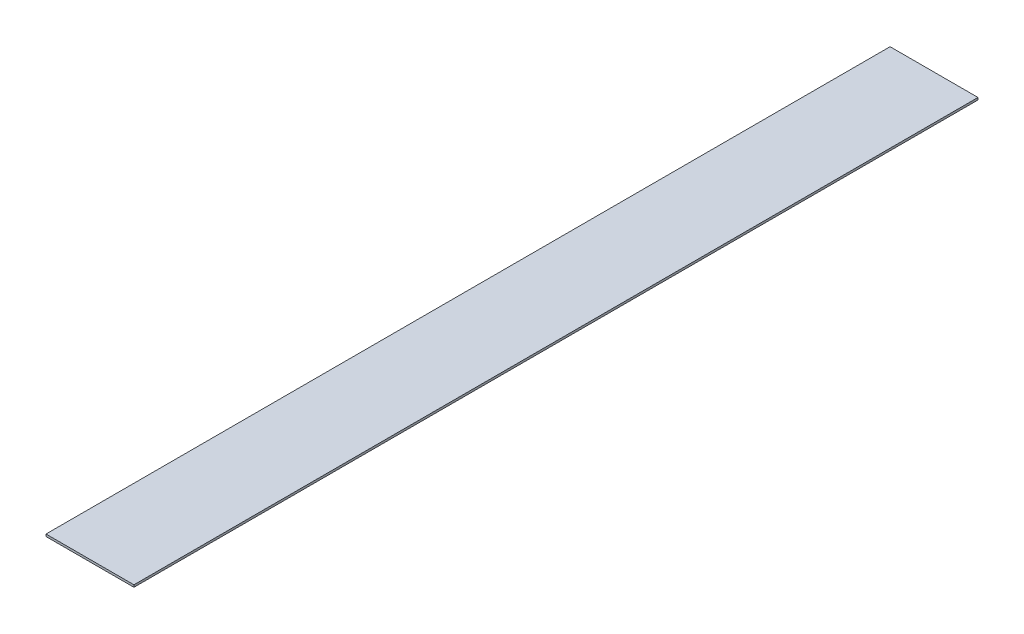
SolidWorks part; units mm, degrees
ref_plane "Спереди" through (0, 0, 0) normal (0, 0, 1) x (1, 0, 0)
ref_plane "Сверху" through (0, 0, 0) normal (0, 1, 0) x (1, 0, 0)
ref_plane "Справа" through (0, 0, 0) normal (1, 0, 0) x (0, 0, -1)
sketch "Эскиз1" plane through (0, 0, 0) normal (0, 0, 1) x (1, 0, 0)
  line L1 (-100, 2.5) -> (100, 2.5)
  line L2 (-100, 2.5) -> (-100, -2.5)
  line L3 (-100, -2.5) -> (100, -2.5)
  line L4 (100, 2.5) -> (100, -2.5)
  line L5 (-100, 2.5) -> (100, -2.5) construction
  line L6 (-100, -2.5) -> (100, 2.5) construction
  point P0 (0, 0)
  dimension "D1" = 5
  dimension "D2" = 200
extrude "Бобышка-Вытянуть1" add sketch "Эскиз1" along normal mid plane 1920
sketch "Эскиз2" plane through (0, -2.5, 0) normal (0, -1, 0) x (1, 0, 0)
  line L0 (0, 960) -> (0, -960) construction
  line L1 (-100, -960) -> (100, -960) construction
  line L2 (-100, 960) -> (100, 960) construction
